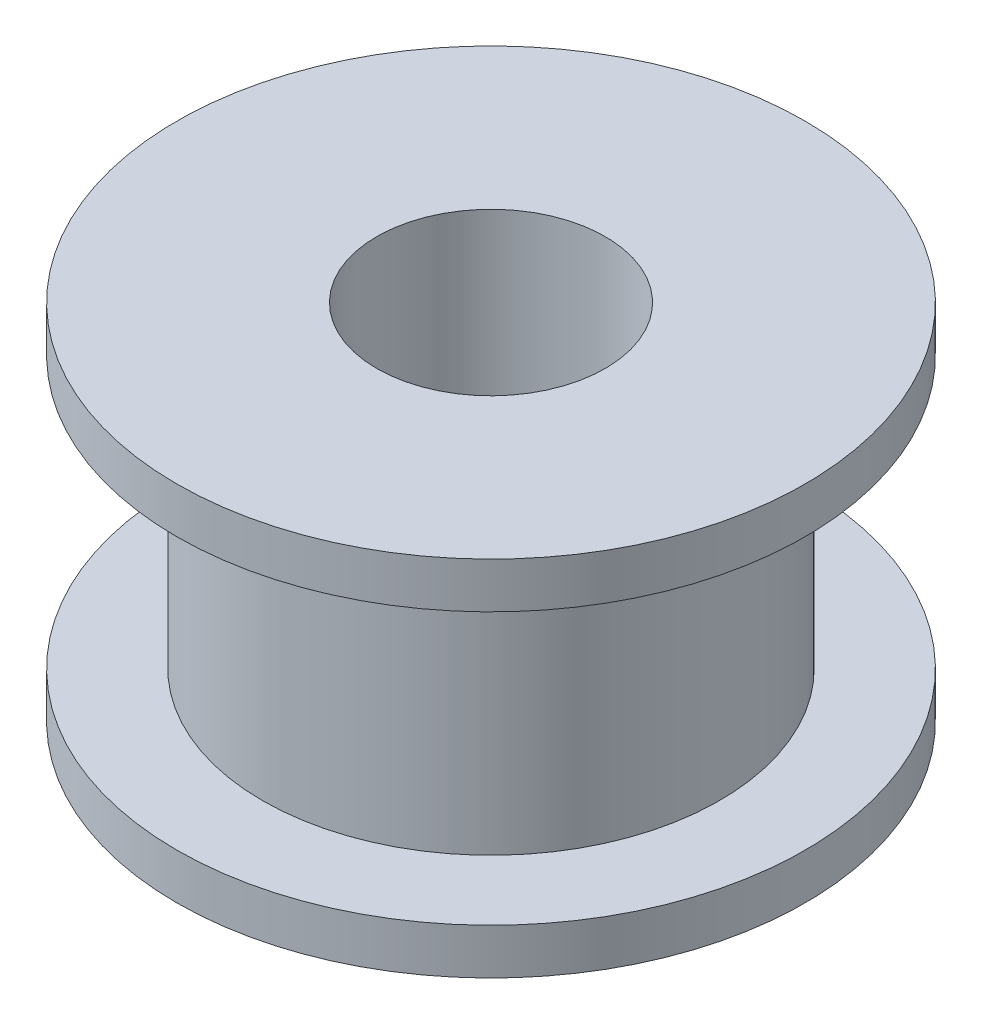
SolidWorks part; units mm, degrees
ref_plane "Front Plane" through (0, 0, 0) normal (0, 0, 1) x (1, 0, 0)
ref_plane "Top Plane" through (0, 0, 0) normal (0, 1, 0) x (1, 0, 0)
ref_plane "Right Plane" through (0, 0, 0) normal (1, 0, 0) x (0, 0, -1)
sketch "Sketch1" plane through (0, 0, 0) normal (0, 1, 0) x (1, 0, 0)
  circle A0 centre (0, 0) radius 11
  dimension "D1" = 22
extrude "Boss-Extrude1" add sketch "Sketch1" along normal blind 1.6
sketch "Sketch2" plane through (0, 1.6, 0) normal (0, 1, 0) x (1, 0, 0)
  circle A0 centre (0, 0) radius 8
  dimension "D1" = 16
extrude "Boss-Extrude2" add sketch "Sketch2" along normal blind 9.5
sketch "Sketch3" plane through (0, 11.1, 0) normal (0, 1, 0) x (1, 0, 0)
  circle A0 centre (0, 0) radius 11
  dimension "D1" = 22
extrude "Boss-Extrude3" add sketch "Sketch3" along normal blind 1.6
sketch "Sketch4" plane through (0, 12.7, 0) normal (0, 1, 0) x (1, 0, 0)
  circle A0 centre (0, 0) radius 4
  dimension "D1" = 8
extrude "Cut-Extrude1" cut sketch "Sketch4" against normal through all both and the other way through all
